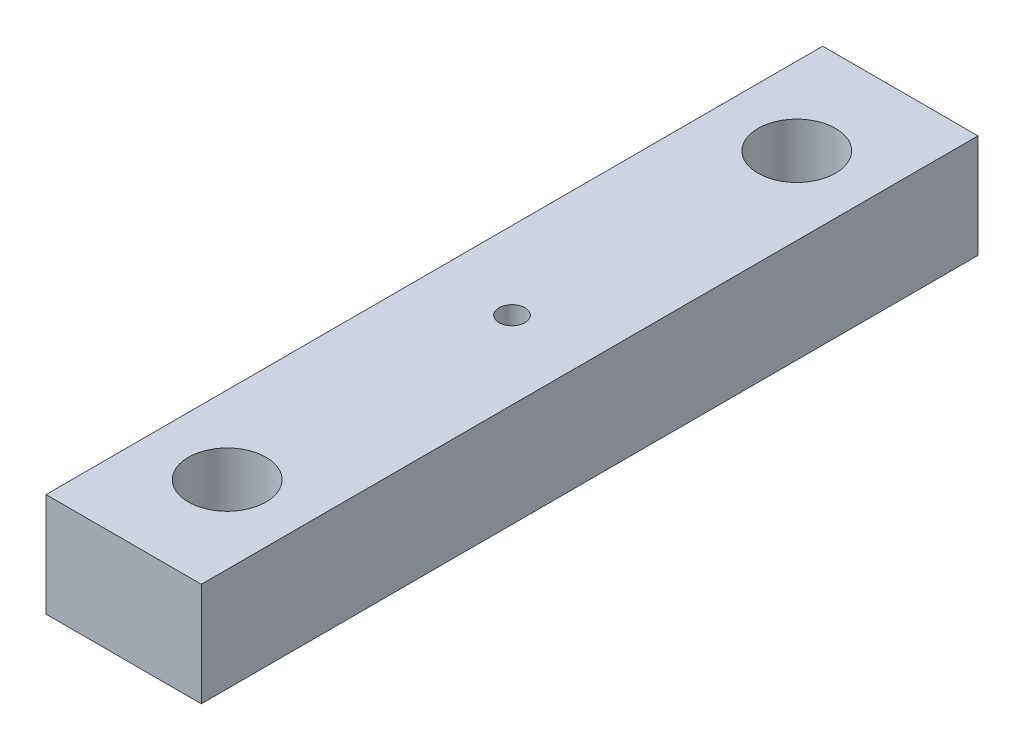
SolidWorks part; units mm, degrees
ref_plane "Front Plane" through (0, 0, 0) normal (0, 0, 1) x (1, 0, 0)
ref_plane "Top Plane" through (0, 0, 0) normal (0, 1, 0) x (1, 0, 0)
ref_plane "Right Plane" through (0, 0, 0) normal (1, 0, 0) x (0, 0, -1)
sketch "Sketch1" plane through (0, 0, 0) normal (0, 1, 0) x (1, 0, 0)
  line L0 (0, 75) -> (0, -75) construction
  line L1 (-15, 75) -> (15, 75)
  line L2 (-15, 75) -> (-15, -75)
  line L3 (-15, -75) -> (15, -75)
  line L4 (15, 75) -> (15, -75)
  circle A0 centre (0, 55) radius 7.5
  circle A1 centre (0, -55) radius 7.5
  circle A2 centre (0, 0) radius 2.5
  point P6 (0, 0)
  dimension "D3" = 15
  dimension "D5" = 5
  dimension "D6" = 20
  dimension "D4" = 20
  dimension "D1" = 30
  dimension "D2" = 150
extrude "Boss-Extrude1" add sketch "Sketch1" along normal blind 20
